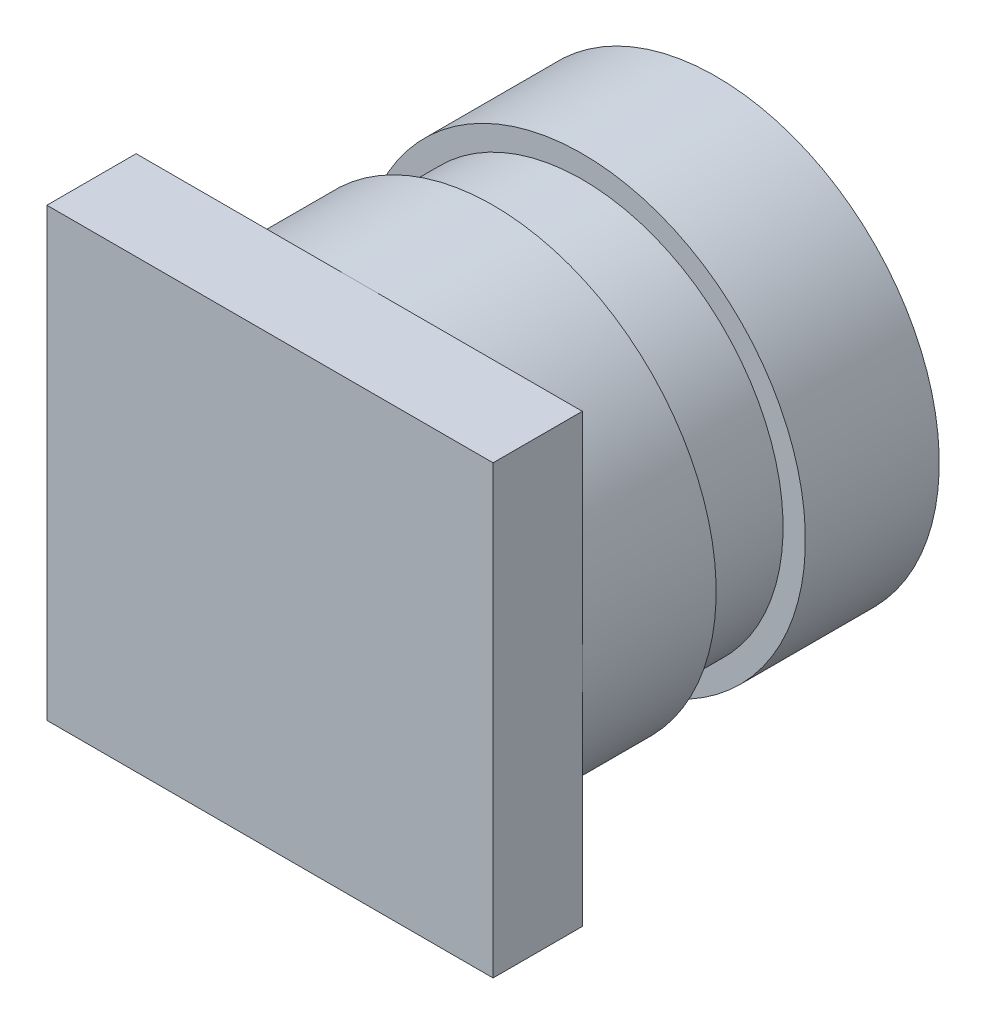
SolidWorks part; units mm, degrees
ref_plane "Plan de face" through (0, 0, 0) normal (0, 0, 1) x (1, 0, 0)
ref_plane "Plan de dessus" through (0, 0, 0) normal (0, 1, 0) x (1, 0, 0)
ref_plane "Plan de droite" through (0, 0, 0) normal (1, 0, 0) x (0, 0, -1)
sketch "Esquisse1" plane through (0, 0, 0) normal (0, 0, 1) x (1, 0, 0)
  line L1 (0, -3.2614) -> (10, -3.2614)
  line L2 (0, -3.2614) -> (0, 6.7386)
  line L3 (0, 6.7386) -> (10, 6.7386)
  line L4 (10, -3.2614) -> (10, 6.7386)
  dimension "D1" = 10
  dimension "D2" = 10
extrude "Boss.-Extru.1" add sketch "Esquisse1" along normal blind 2
sketch "Esquisse2" plane through (0, 0, 0) normal (0, 0, -1) x (-1, 0, 0)
  line L0 (-10, 6.7386) -> (0, -3.2614)
  line L1 (-10, 6.7386) -> (0, 6.7386)
  line L2 (-10, 6.7386) -> (-10, -3.2614)
  line L3 (-10, -3.2614) -> (0, -3.2614)
  line L4 (0, 6.7386) -> (0, -3.2614)
  circle A0 centre (-5, 1.7386) radius 5
  dimension "D1" = 10
  dimension "D2" = 10
extrude "Boss.-Extru.2" add sketch "Esquisse2" along normal blind 3 contours L0 A0 | A0 L0
sketch "Esquisse3" plane through (0, 0, -3) normal (0, 0, -1) x (-1, 0, 0)
  circle A0 centre (-5, 1.7386) radius 4.5
extrude "Boss.-Extru.3" add sketch "Esquisse3" along normal blind 2
sketch "Esquisse4" plane through (0, 0, -5) normal (0, 0, -1) x (-1, 0, 0)
  line L0 (-10, 6.7386) -> (0, -3.2614)
  circle A0 centre (-5, 1.7386) radius 5
  circle M1 centre (-5, 1.7386) radius 4.5
extrude "Boss.-Extru.5" add sketch "Esquisse4" along normal blind 3 contours L0 A0 M1 | L0 A0 M1 | L0 M1 | L0 M1
sketch "Esquisse5" plane through (0, 0, -8) normal (0, 0, -1) x (-1, 0, 0)
  line L0 (-10, 6.7386) -> (0, -3.2614)
  circle A0 centre (-5, 1.7386) radius 4.5
extrude "Enlèv. mat.-Extru.1" cut sketch "Esquisse5" against normal blind 1 contours L0 A0 | L0 A0
